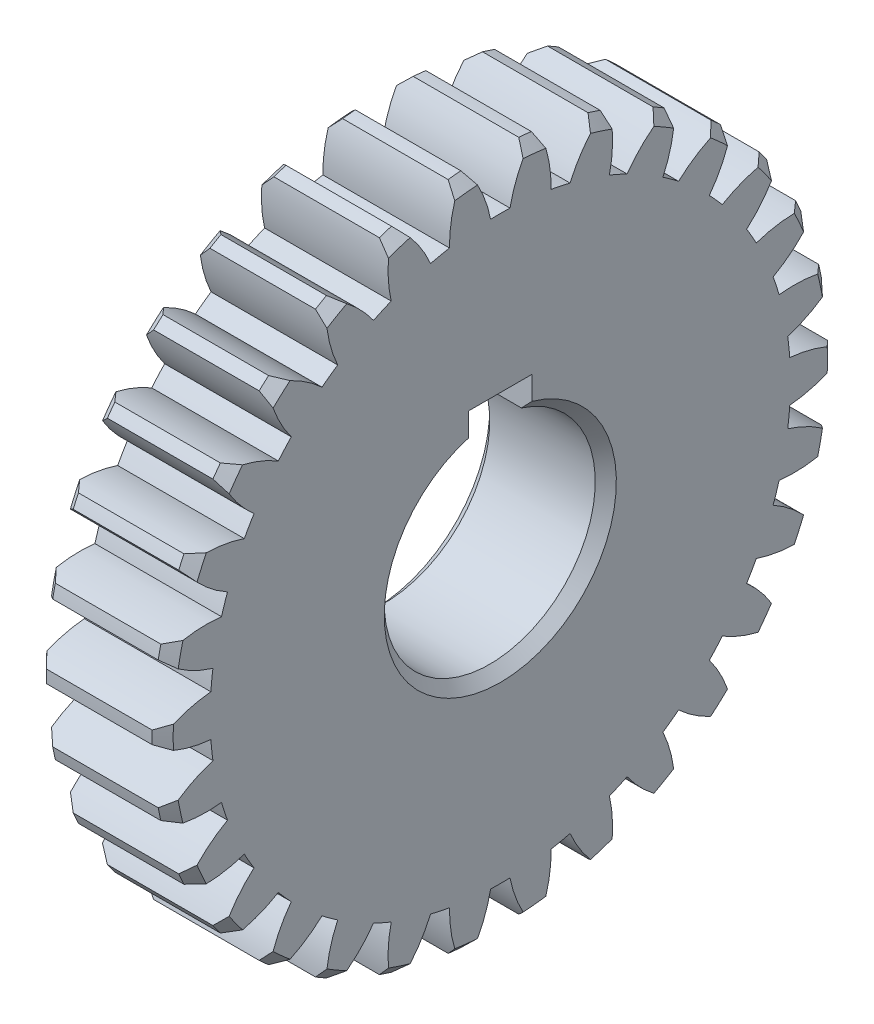
SolidWorks part; units mm, degrees
ref_plane "Plane1" through (0, 0, 0) normal (0, 0, 1) x (1, 0, 0)
ref_plane "Plane2" through (0, 0, 0) normal (0, 1, 0) x (1, 0, 0)
ref_plane "Plane3" through (0, 0, 0) normal (1, 0, 0) x (0, 0, -1)
sketch "HoldingSke" plane through (0, 0, 0) normal (0, 1, 0) x (1, 0, 0)
  line L0 (0, 0) -> (0.433, -0.25)
  line L1 (-15, 0) -> (100, 0) construction
  line L2 (0, 0) -> (-2.1039, 2.3779)
  line L3 (0, 0) -> (-11.863, 4.5341)
  line L4 (0, 0) -> (7.479, 4.318)
  line L5 (0, 0) -> (-46.8476, -17.4728)
  line L6 (0, 0) -> (-9.9476, -6.7116)
  line L7 (-2.1039, 2.3779) -> (8.6586, 51.2059)
  line L8 (-76.2, 54.61) -> (-73.4, 54.61)
  line L9 (-71.009, 38.7566) -> (-53.1078, 45.2721)
  line L10 (-76.2, 71.12) -> (104.1128, 71.12)
  line L11 (0, 0) -> (-12, 0)
  line L12 (-76.2, 101.6) -> (-76.133, 101.6)
  line L13 (24.9733, 27.94) -> (52.9518, 28.4284)
  line L14 (24.9733, 27.94) -> (24.9743, 27.94)
  line L15 (24.9733, 27.94) -> (100.4006, 29.5858)
  line L16 (-63.627, -2) -> (-12.827, -2)
  circle A0 centre (0, 0) radius 10
  circle A1 centre (0, 0) radius 27.499
  circle A2 centre (0, 0) radius 37.5
  circle A3 centre (0, 0) radius 10
  dimension "MHD" = 54.998
  dimension "Hub_dia" = 75
  dimension "Bore" = 20
  dimension "MBD" = 20
  dimension "Num_teeth" = 30
  dimension "Pitch" = 0.5
  dimension "Overall_len" = 50
  dimension "Show_teeth" = 30
  dimension "Thickness" = 12
  dimension "OAL" = 50.0001
  dimension "T_dim" = 2.8
  dimension "Ap" = 20
  dimension "H" = 19.05
  dimension "Pitch_radius" = 180.3128
  dimension "Width" = 12
  dimension "Backlash" = 0.067
  dimension "Addendum_fac" = 1
  dimension "Dedendum_fac" = 1.25
  dimension "Clearance_fac" = 0.25
  dimension "Dedendum_add" = 0.001
  dimension "Module" = 2
sketch "BasProSke" plane through (0, 0, 0) normal (0, 1, 0) x (1, 0, 0)
  line L0 (-10, 0) -> (60, 0) construction
  line L1 (0, 0) -> (0, 32)
  line L2 (0, 0) -> (12, 0)
  line L3 (12, 0) -> (12, 32)
  line L4 (12, 32) -> (0, 32)
  dimension "Thickness" = 12
  dimension "Diameter" = 64
revolve "Base-Revolve" add sketch "BasProSke" angle 360 about L0
sketch "TooCutSke" plane through (0, 0, 0) normal (1, 0, 0) x (0, 0, -1)
  line L1 (0, 0) -> (0, 107) construction
  line L2 (0, 0) -> (-1.6873, 29.9525) construction
  line L3 (0, 0) -> (-6.2643, 59.6013) construction
  line L4 (-1.6873, 29.9525) -> (-3.1322, 29.8007) construction
  arc A0 (0.9186, 27.4837) -> (-0.9186, 27.4837) centre (0, 0) ccw
  arc A1 (2.7618, 31.9061) -> (-2.7618, 31.9061) centre (0, 0) ccw
  circle A2 centre (0, 0) radius 30 construction
  circle A3 centre (0, 0) radius 28.1908 construction
  arc A4 (-0.9186, 27.4837) -> (-2.7618, 31.9061) centre (-12.6936, 25.1712) ccw
  arc A5 (2.7618, 31.9061) -> (0.9186, 27.4837) centre (12.6936, 25.1712) ccw
  dimension "Root_dia" = 54.998
  dimension "Overcut_dia" = 64.0508
  dimension "Pitch_dia" = 60
  dimension "Base_dia" = 56.3816
  dimension "Flank_rad" = 12
  dimension "Half_ang" = 6
  dimension "Half_CT" = 1.4528
extrude "ToothCut" cut sketch "TooCutSke" along normal through all
fillet "Breaks" [suppressed] radius 0.04
fillet "RootFillets" [suppressed] radius 0.501
pattern_circular "TeethCuts" count 30 every 12 about axis through (-10, 0, 0) along (1, 0, 0) of "ToothCut", "RootFillets", "Breaks"
sketch "HubNeaOneSke" plane through (0, 0, 0) normal (-1, 0, 0) x (0, 0, 1)
  circle A0 centre (0, 0) radius 27.499
  dimension "Diameter" = 54.998
extrude "HubNearOne" [suppressed] add sketch "HubNeaOneSke" along normal blind 38.0001
sketch "HubNeaBotSke" plane through (0, 0, 0) normal (-1, 0, 0) x (0, 0, 1)
  circle A0 centre (0, 0) radius 27.499
  dimension "Diameter" = 54.998
extrude "HubNearBoth" [suppressed] add sketch "HubNeaBotSke" along normal blind 19
ref_plane "FarPln" through (12, 0, 0) normal (1, 0, 0) x (0, 0, -1)
sketch "HubFarSke" plane through (12, 0, 0) normal (1, 0, 0) x (0, 0, -1)
  circle A0 centre (0, 0) radius 27.499
  dimension "Diameter" = 54.998
extrude "HubFar" [suppressed] add sketch "HubFarSke" along normal blind 19
sketch "BorSke" plane through (0, 0, 0) normal (1, 0, 0) x (0, 0, -1)
  circle A0 centre (0, 0) radius 10
  dimension "Diameter" = 20
extrude "Bore" cut sketch "BorSke" along normal mid plane 100.0001
sketch "KeySke" plane through (0, 0, 0) normal (1, 0, 0) x (0, 0, -1)
  line L0 (-3, 0) -> (-3, 12.8)
  line L1 (-3, 12.8) -> (3, 12.8)
  line L2 (3, 12.8) -> (3, 0)
  line L3 (0, 0) -> (0, 34) construction
  line L4 (-3, 0) -> (3, 0)
  dimension "Offset" = 12.8
  dimension "Width" = 6
extrude "Keyway" cut sketch "KeySke" along normal mid plane 100.0001
pattern_circular "Keyway2" [suppressed] count 2 every 90 about axis through (-10, 0, 0) along (1, 0, 0)
chamfer "Chamfer1" distance 1 angle 45 62 edges at (12, 27.7128, 16) (12, 30.4338, 9.8885) (12, 31.8247, 3.3449) (12, 31.8247, -3.3449) (12, 30.4338, -9.8885) (12, 27.7128, -16) (12, 23.7806, -21.4122) (12, 18.8091, -25.8885) (12, 13.0156, -29.2335) (12, 6.6532, -31.3007) (12, 0, -32) (12, -6.6532, -31.3007) (12, -13.0156, -29.2335) (12, -18.8091, -25.8885) (12, -23.7806, -21.4122) (12, -27.7128, -16) (12, -30.4338, -9.8885) (12, -31.8247, -3.3449) (12, -31.8247, 3.3449) (12, -30.4338, 9.8885) (12, -27.7128, 16) (12, -23.7806, 21.4122) (12, -18.8091, 25.8885) (12, -13.0156, 29.2335) (12, -6.6532, 31.3007) (12, 0, 32) (12, 6.6532, 31.3007) (12, 13.0156, 29.2335) (12, 18.8091, 25.8885) (12, 23.7806, 21.4122) (0, 23.7806, 21.4122) (0, 18.8091, 25.8885) (0, 13.0156, 29.2335) (0, 6.6532, 31.3007) (0, 0, 32) (0, -6.6532, 31.3007) (0, -13.0156, 29.2335) (0, -18.8091, 25.8885) (0, -23.7806, 21.4122) (0, -27.7128, 16) (0, -30.4338, 9.8885) (0, -31.8247, 3.3449) (0, -31.8247, -3.3449) (0, -30.4338, -9.8885) (0, -27.7128, -16) (0, -23.7806, -21.4122) (0, -18.8091, -25.8885) (0, -13.0156, -29.2335) (0, -6.6532, -31.3007) (0, 0, -32) (0, 6.6532, -31.3007) (0, 13.0156, -29.2335) (0, 18.8091, -25.8885) (0, 23.7806, -21.4122) (0, 27.7128, -16) (0, 30.4338, -9.8885) (0, 31.8247, -3.3449) (0, 27.7128, 16) (0, 30.4338, 9.8885) (0, 31.8247, 3.3449) (12, -10, 0) (0, -10, 0)
equation "' \"Module@HoldingSke\" = 6.35"
equation "' \"Num_teeth@HoldingSke\" = 12"
equation "' \"Ap@HoldingSke\" =  20"
equation "' \"Ap@HoldingSke\" = 20"
equation "' \"Width@HoldingSke\" = 0.5 * 25.4"
equation "' \"Hub_dia@HoldingSke\"= 1 * 25.4"
equation "' \"Hub_dia@HoldingSke\" = 1 * 25.4"
equation "' \"Overall_len@HoldingSke\" = 1.0 * 25.4"
equation "' \"Bore@HoldingSke\" = 0.75 * 25.4"
equation "' \"T_dim@HoldingSke\" = 0.1 * 25.4"
equation "' \"Width@KeySke\" = 0.25 * 25.4"
equation "' \"Show_teeth@HoldingSke\" = 13"
equation "' \"Backlash@HoldingSke\" = 0.009 * 25.4"
equation "' \"Addendum_fac@HoldingSke\" = 1.0"
equation "' \"Dedendum_fac@HoldingSke\" = 1.25"
equation "' \"Dedendum_add@HoldingSke\" = 0.00005 * 25.4"
equation "' \"Clearance_fac@HoldingSke\" = 0.25"
equation "\"Pitch@HoldingSke\" = 1 / \"Module@HoldingSke\""
equation "\"Overcut_dia@TooCutSke\" = (\"Num_teeth@HoldingSke\" + 2 * \"Addendum_fac@HoldingSke\") / \"Pitch@HoldingSke\" + 0.002 * 25.4"
equation "\"Pitch_dia@TooCutSke\" = \"Num_teeth@HoldingSke\" / \"Pitch@HoldingSke\""
equation "\"Base_dia@TooCutSke\" = \"Num_teeth@HoldingSke\" / \"Pitch@HoldingSke\" * cos((\"Ap@HoldingSke\"  * 3.14159265 / 180))"
equation "\"Root_dia@TooCutSke\" = (\"Num_teeth@HoldingSke\" + 2) / \"Pitch@HoldingSke\" - 2 * (\"Addendum_fac@HoldingSke\" + \"Dedendum_fac@HoldingSke\") / \"Pitch@HoldingSke\" - \"Dedendum_add@HoldingSke\" * 2"
equation "\"Half_ang@TooCutSke\" = 180 / \"Num_teeth@HoldingSke\""
equation "\"Half_CT@TooCutSke\" = \"Num_teeth@HoldingSke\" / \"Pitch@HoldingSke\" * sin((3.14159265 / 2 / \"Num_teeth@HoldingSke\")) / 2 - 7 * \"Backlash@HoldingSke\" / 4"
equation "\"Flank_rad@TooCutSke\" = \"Num_teeth@HoldingSke\" / \"Pitch@HoldingSke\" / 5"
equation "\"Radius@RootFillets\" = \"Clearance_fac@HoldingSke\" / \"Pitch@HoldingSke\" + \"Dedendum_add@HoldingSke\""
equation "\"Break_rad@Breaks\" = 0.02 / \"Pitch@HoldingSke\""
equation "\"Thickness@HoldingSke\" = \"Width@HoldingSke\""
equation "\"OAL@HoldingSke\" = \"Thickness@HoldingSke\""
equation "\"MHD@HoldingSke\" = (\"Num_teeth@HoldingSke\" + 2) / \"Pitch@HoldingSke\" - 2 * (\"Addendum_fac@HoldingSke\" + \"Dedendum_fac@HoldingSke\")  / \"Pitch@HoldingSke\" - \"Dedendum_add@HoldingSke\" * 2"
equation "\"MBD@HoldingSke\" = (\"Num_teeth@HoldingSke\" + 2) / \"Pitch@HoldingSke\" - 2 * (\"Addendum_fac@HoldingSke\" + \"Dedendum_fac@HoldingSke\")  / \"Pitch@HoldingSke\" - \"Dedendum_add@HoldingSke\" * 2 - 0.002 * 25.4"
equation "\"MHD@HoldingSke\" = ((sgn( \"MHD@HoldingSke\" - \"Hub_dia@HoldingSke\" )-1)*( \"MHD@HoldingSke\" - \"Hub_dia@HoldingSke\" ))/-2+ \"Hub_dia@HoldingSke\""
equation "\"MBD@HoldingSke\" = ((sgn( \"MBD@HoldingSke\" - \"Bore@HoldingSke\" )-1)*( \"MBD@HoldingSke\" - \"Bore@HoldingSke\" ))/-2+ \"Bore@HoldingSke\""
equation "\"OAL@HoldingSke\" = ((sgn( \"OAL@HoldingSke\" - \"Overall_len@HoldingSke\" )+1)*( \"OAL@HoldingSke\" - \"Overall_len@HoldingSke\" ))/2 + \"Overall_len@HoldingSke\" + 0.000002 * 25.4"
equation "\"Num_teeth@TeethCuts\" = int( \"Show_teeth@HoldingSke\" ) + 1"
equation "\"Num_teeth@TeethCuts\" = ((sgn( \"Num_teeth@TeethCuts\" - \"Num_teeth@HoldingSke\" )-1)*( \"Num_teeth@TeethCuts\" - \"Num_teeth@HoldingSke\" ))/-2+ \"Num_teeth@HoldingSke\""
equation "\"Num_teeth@TeethCuts\" = ((sgn( \"Num_teeth@TeethCuts\" - 2.0)+1)*( \"Num_teeth@TeethCuts\" - 2.0))/2 +2.0"
equation "\"Angle@TeethCuts\" = 360.0 / \"Num_teeth@HoldingSke\""
equation "\"Diameter@BasProSke\" = (\"Num_teeth@HoldingSke\" + 2 * \"Addendum_fac@HoldingSke\") / \"Pitch@HoldingSke\""
equation "\"Thickness@BasProSke\"  = \"Thickness@HoldingSke\""
equation "' \"Fillet_rad@BasProSke\" =  \"Thickness@HoldingSke\" * 0.05"
equation "' \"Fillet_rad@BasProSke\" = \"Thickness@HoldingSke\" * 0.05"
equation "\"MHD@HoldingSke\" = ((sgn( \"MHD@HoldingSke\" - \"Root_dia@TooCutSke\" )-1)*( \"MHD@HoldingSke\" - \"Root_dia@TooCutSke\" ))/-2+ \"Root_dia@TooCutSke\""
equation "\"Diameter@HubNeaOneSke\" = \"MHD@HoldingSke\""
equation "\"Length@HubNearOne\" = \"OAL@HoldingSke\" - \"Thickness@BasProSke\""
equation "\"Diameter@HubNeaBotSke\" = \"MHD@HoldingSke\""
equation "\"Length@HubNearBoth\" = ( \"OAL@HoldingSke\" - \"Thickness@BasProSke\" ) / 2.0"
equation "\"Thickness@FarPln\" = \"Thickness@BasProSke\""
equation "\"Diameter@HubFarSke\" = \"MHD@HoldingSke\""
equation "\"Length@HubFar\" = ( \"OAL@HoldingSke\" - \"Thickness@BasProSke\" ) / 2.0"
equation "\"Diameter@BorSke\" = \"MBD@HoldingSke\""
equation "\"D1@Bore\" = \"OAL@HoldingSke\" * 2.0"
equation "\"D1@Keyway\" = \"OAL@HoldingSke\" * 2.0"
equation "\"Offset@KeySke\" = \"T_dim@HoldingSke\" + \"MBD@HoldingSke\" / 2.0"
